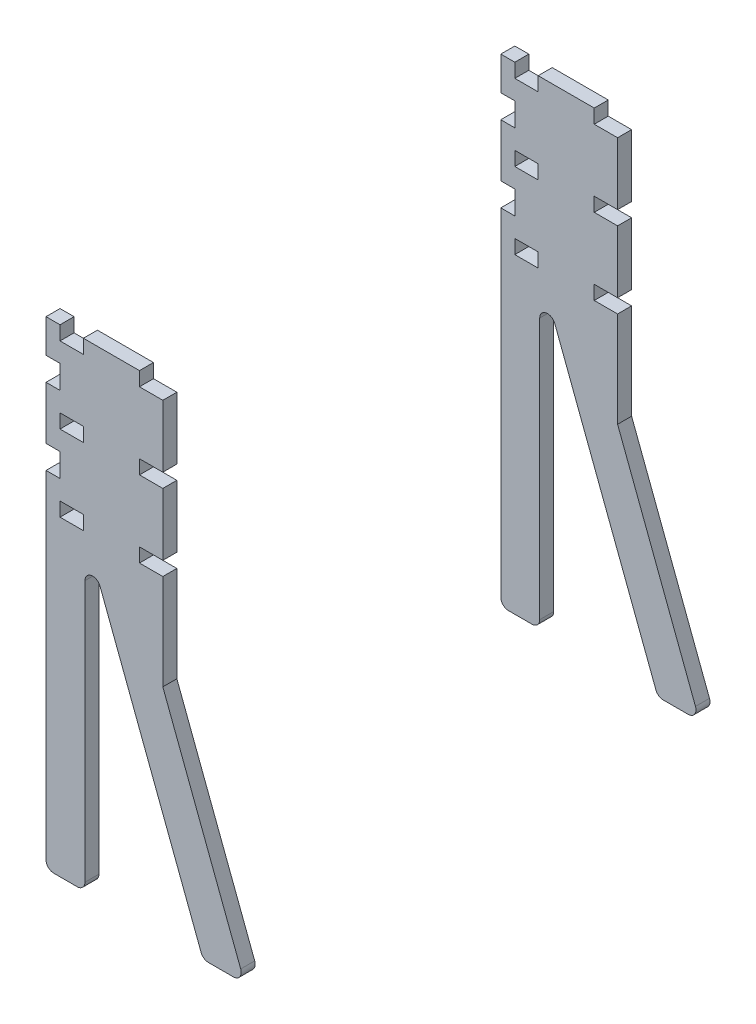
SolidWorks part; units mm, degrees
ref_plane "Plan de face" through (0, 0, 0) normal (0, 0, 1) x (1, 0, 0)
ref_plane "Plan de dessus" through (0, 0, 0) normal (0, 1, 0) x (1, 0, 0)
ref_plane "Plan de droite" through (0, 0, 0) normal (1, 0, 0) x (0, 0, -1)
sketch "Esquisse1" plane through (0, 0, 0) normal (0, 0, 1) x (1, 0, 0)
  line L0 (10, 0) -> (40, 0)
  line L1 (50, 10) -> (50, 345.4191)
  line L2 (69.3505, 348.9644) -> (199.2151, 6.4547)
  line L3 (208.5655, 0) -> (240.6495, 0)
  line L4 (250, 13.5453) -> (150, 277.2889)
  line L5 (150, 277.2889) -> (150, 614)
  line L6 (150, 614) -> (0, 614)
  line L7 (0, 614) -> (0, 10)
  line L8 (50, 400) -> (150, 400) construction
  line L9 (50, 400) -> (0, 400) construction
  line L10 (50, 345.4191) -> (50, 400) construction
  line L11 (50, 400) -> (69.3505, 348.9644) construction
  arc A0 (50, 345.4191) -> (69.3505, 348.9644) centre (60, 345.4191) cw
  arc A1 (10, 0) -> (0, 10) centre (10, 10) cw
  arc A2 (40, 0) -> (50, 10) centre (40, 10) ccw
  arc A3 (199.2151, 6.4547) -> (208.5655, 0) centre (208.5655, 10) ccw
  arc A4 (240.6495, 0) -> (250, 13.5453) centre (240.6495, 10) ccw
  point P16 (0, 0)
  dimension "D4" = 10
  dimension "D1" = 150
  dimension "D2" = 50
  dimension "D3" = 50
  dimension "D5" = 250
  dimension "D6" = 400
  dimension "D7" = 214
extrude "Boss.-Extru.1" add sketch "Esquisse1" along normal blind 18
pattern_linear "Répétition linéaire1" count 2 spacing 584 along (0, 0, -1) of "Boss.-Extru.1"
sketch "Esquisse2" plane through (0, 0, 18) normal (0, 0, 1) x (1, 0, 0)
  line L0 (18, 614) -> (18, 764) construction
  line L1 (18, 571) -> (0, 571)
  line L2 (18, 571) -> (18, 541)
  line L3 (18, 541) -> (0, 541)
  line L4 (0, 571) -> (0, 541)
  line L5 (0, 614) -> (0, 10) construction
  line L6 (18, 596) -> (18, 516) construction
  line L7 (18, 473) -> (0, 473)
  line L8 (18, 473) -> (18, 443)
  line L9 (18, 443) -> (0, 443)
  line L10 (0, 473) -> (0, 443)
  line L11 (18, 498) -> (18, 418) construction
  line L12 (150, 614) -> (0, 614) construction
  line L13 (48, 596) -> (18, 596)
  line L14 (48, 596) -> (48, 614)
  line L15 (48, 614) -> (18, 614)
  line L16 (18, 596) -> (18, 614)
  line L17 (18, 596) -> (18, 614) construction
  line L18 (150, 277.2889) -> (150, 614) construction
  line L19 (120, 596) -> (150, 596)
  line L20 (120, 596) -> (120, 614)
  line L21 (120, 614) -> (150, 614)
  line L22 (150, 596) -> (150, 614)
  line L23 (18, 516) -> (48, 516)
  line L24 (18, 516) -> (18, 498)
  line L25 (18, 498) -> (48, 498)
  line L26 (48, 516) -> (48, 498)
  line L27 (150, 516) -> (120, 516)
  line L28 (150, 516) -> (150, 498)
  line L29 (150, 498) -> (120, 498)
  line L30 (120, 516) -> (120, 498)
  line L31 (120, 516) -> (150, 516) construction
  line L32 (120, 418) -> (150, 418) construction
  line L33 (150, 418) -> (120, 418)
  line L34 (150, 418) -> (150, 400)
  line L35 (150, 400) -> (120, 400)
  line L36 (120, 418) -> (120, 400)
  line L38 (48, 418) -> (18, 418)
  line L39 (48, 418) -> (48, 400)
  line L40 (48, 400) -> (18, 400)
  line L41 (18, 418) -> (18, 400)
  point P22 (18, 458)
  point P23 (18, 556)
  dimension "D1" = 30
extrude "Enlèv. mat.-Extru.1" cut sketch "Esquisse2" against normal through all
